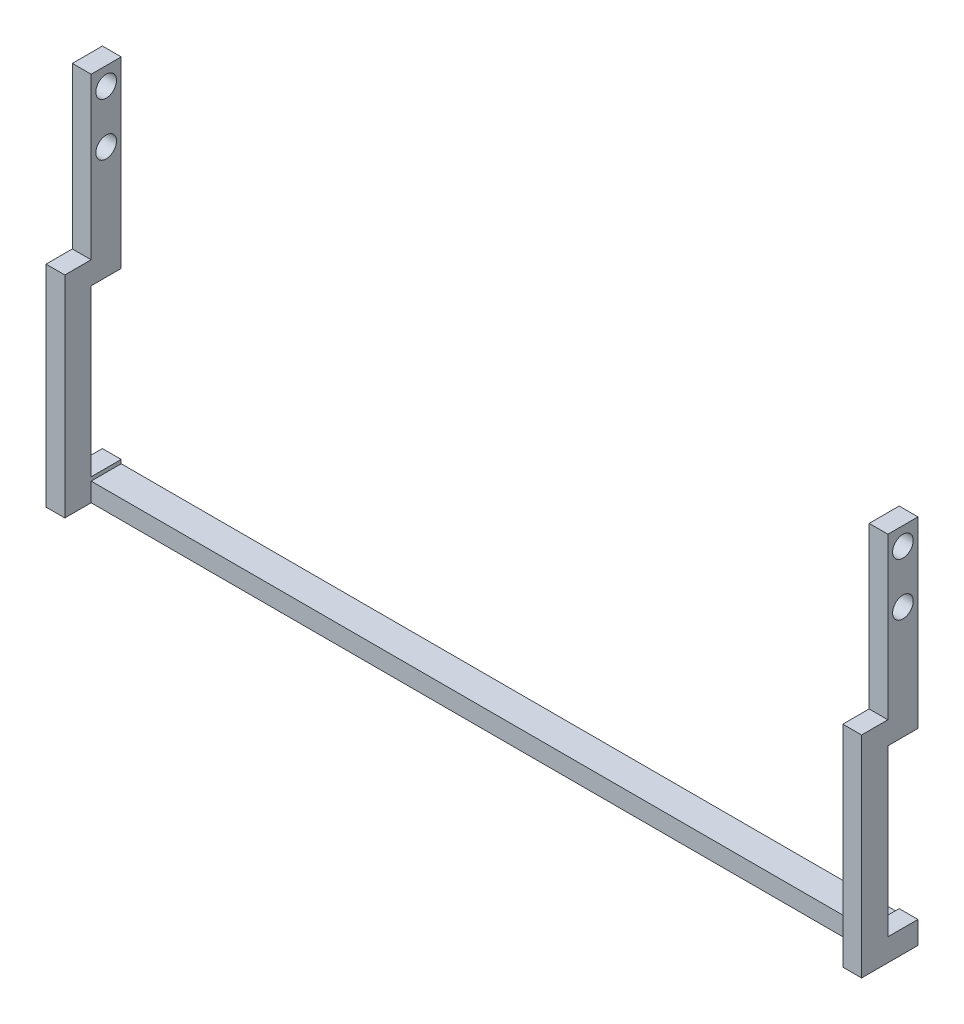
SolidWorks part; units mm, degrees
other "Marca1"
sketch "Croquis6" plane through (1063.495, 228.0391, 43.3509) normal (-1, 0, 0) x (0, 0, 1)
material "7075-T6 (SN)"
ref_plane "Alzado" through (0, 0, 0) normal (0, 0, 1) x (1, 0, 0)
ref_plane "Planta" through (0, 0, 0) normal (0, 1, 0) x (1, 0, 0)
ref_plane "Vista lateral" through (0, 0, 0) normal (1, 0, 0) x (0, 0, -1)
sketch "Croquis1" plane through (0, 0, 0) normal (0, 0, 1) x (1, 0, 0)
  line L0 (0, 0) -> (2170, 0)
  line L1 (0, 0) -> (0, 990)
  line L2 (0, 990) -> (50, 990)
  line L3 (2170, 0) -> (2170, 990)
  line L4 (2170, 990) -> (2120, 990)
  line L5 (50, 990) -> (50, 50)
  line L6 (50, 50) -> (2120, 50)
  line L7 (2120, 50) -> (2120, 990)
  dimension "D1" = 2170
  dimension "D2" = 990
  dimension "D3" = 50
  dimension "D4" = 990
  dimension "D5" = 50
  dimension "D6" = 50
extrude "Saliente-Extruir1" add sketch "Croquis1" along normal blind 80
sketch "Croquis2" plane through (0, 0, 0) normal (-1, 0, 0) x (0, 0, 1)
  line L0 (40, 990) -> (40, 800) construction
  line L1 (80, 990) -> (0, 990) construction
  circle A0 centre (40, 940) radius 27.5
  circle A1 centre (40, 800) radius 27.5
  dimension "D1" = 55
  dimension "D3" = 55
  dimension "D2" = 50
  dimension "D4" = 140
extrude "Cortar-Extruir2" cut sketch "Croquis2" against normal through all
sketch "Croquis3" plane through (0, 0, 0) normal (-1, 0, 0) x (0, 0, 1)
  line L0 (80, 990) -> (80, 0) construction
  line L1 (80, 560) -> (150, 560)
  line L2 (80, 500) -> (80, 60)
  line L5 (0, 500) -> (80, 500)
  line L6 (0, 990) -> (0, 0) construction
  line L7 (0, 500) -> (0, 560)
  line L8 (0, 560) -> (80, 560)
  line L9 (0, 0) -> (150, 0)
  line L11 (0, 0) -> (0, 60)
  line L12 (0, 60) -> (80, 60)
  line L14 (150, 0) -> (150, 560)
  dimension "D1" = 70
  dimension "D2" = 60
  dimension "D3" = 60
  dimension "D4" = 80
  dimension "D5" = 560
extrude "Saliente-Extruir2" add sketch "Croquis3" against normal blind 50
sketch "Croquis4" plane through (0, 0, 0) normal (-1, 0, 0) x (0, 0, 1)
  line L1 (0, 500) -> (80, 500)
  line L2 (0, 500) -> (0, 60)
  line L3 (0, 60) -> (80, 60)
  line L4 (80, 500) -> (80, 60)
extrude "Cortar-Extruir3" cut sketch "Croquis4" against normal through all
sketch "Croquis5" plane through (2170, 0, 0) normal (1, 0, 0) x (0, 0, -1)
  line L0 (-150, 50) -> (-150, 0)
  line L1 (0, 500) -> (-80, 500)
  line L2 (0, 500) -> (0, 560)
  line L3 (0, 560) -> (-150, 560)
  line L5 (0, 60) -> (-80, 60)
  line L6 (0, 60) -> (0, 0)
  line L10 (-150, 560) -> (-150, 50)
  line L12 (-80, 500) -> (-80, 60)
  line L13 (-150, 0) -> (0, 0)
extrude "Saliente-Extruir3" add sketch "Croquis5" against normal blind 50
scale "Escala1" scale about centroid uniform scaling yes scale factor 0.063
sketch "Croquis9" plane through (0, 284.6958, 0) normal (0, 1, 0) x (1, 0, 0)
  line L1 (1016.645, -54.5641) -> (1153.355, -54.5641)
  line L2 (1016.645, -54.5641) -> (1016.645, -59.6041)
  line L3 (1016.645, -59.6041) -> (1153.355, -59.6041)
  line L4 (1153.355, -54.5641) -> (1153.355, -59.6041)
extrude "Saliente-Extruir5" add sketch "Croquis9" along normal blind 13
sketch "Croquis10" plane through (0, 0, 59.6041) normal (0, 0, 1) x (1, 0, 0)
  line L0 (1150.205, 284.6958) -> (1150.205, 257.6058) construction
  line L1 (1019.795, 284.6958) -> (1150.205, 284.6958)
  line L2 (1019.795, 284.6958) -> (1019.795, 292.6958)
  line L3 (1019.795, 292.6958) -> (1150.205, 292.6958)
  line L4 (1150.205, 284.6958) -> (1150.205, 292.6958)
  dimension "D1" = 8
extrude "Cortar-Extruir4" cut sketch "Croquis10" against normal blind 10
sketch "Croquis11" plane through (0, 0, 59.6041) normal (0, 0, 1) x (1, 0, 0)
  line L0 (1153.355, 257.6058) -> (1153.355, 297.6958) construction
  line L1 (1016.645, 297.6958) -> (1153.355, 297.6958)
  line L2 (1016.645, 297.6958) -> (1016.645, 284.5458)
  line L3 (1016.645, 284.5458) -> (1153.355, 284.5458)
  line L4 (1153.355, 297.6958) -> (1153.355, 284.5458)
  dimension "D1" = 13.15
extrude "Cortar-Extruir5" cut sketch "Croquis11" against normal through all
sketch "Croquis12" plane through (1150.205, 0, 0) normal (-1, 0, 0) x (0, 0, 1)
  line L0 (57.0841, 283.3868) -> (57.0841, 284.5458)
  line L1 (54.5641, 284.5458) -> (59.6041, 284.5458) construction
  line L2 (59.6041, 283.3868) -> (57.0841, 283.3868)
  line L3 (59.6041, 284.5458) -> (57.0841, 284.5458)
  line L4 (59.6041, 284.5458) -> (59.6041, 283.3868)
